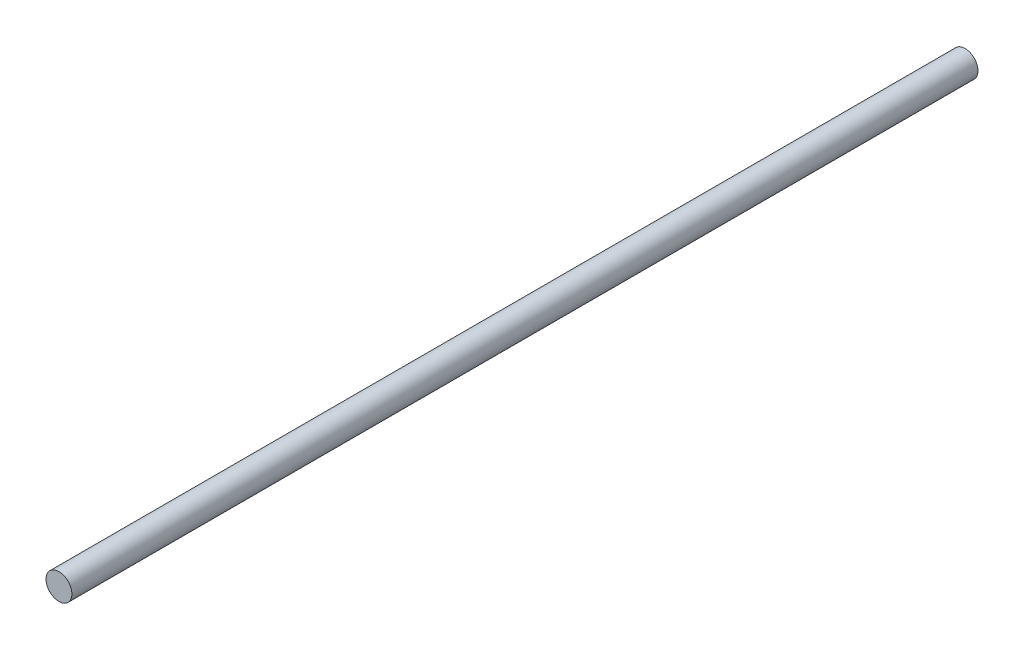
SolidWorks part; units mm, degrees
ref_plane "Plan de face" through (0, 0, 0) normal (0, 0, 1) x (1, 0, 0)
ref_plane "Plan de dessus" through (0, 0, 0) normal (0, 1, 0) x (1, 0, 0)
ref_plane "Plan de droite" through (0, 0, 0) normal (1, 0, 0) x (0, 0, -1)
sketch "Esquisse1" plane through (0, 0, 0) normal (0, 0, 1) x (1, 0, 0)
  circle A0 centre (0, 0) radius 1.5
  dimension "D1" = 3
extrude "Boss.-Extru.1" add sketch "Esquisse1" along normal blind 105
